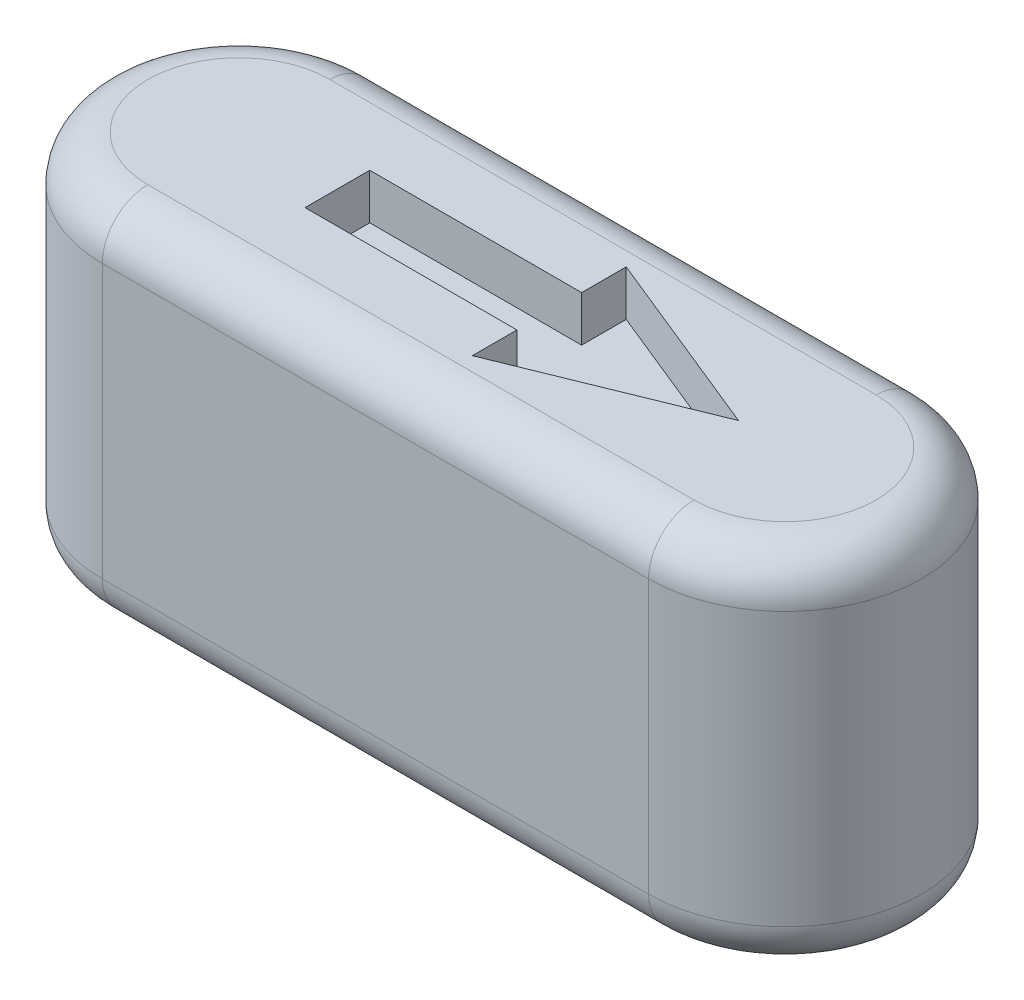
SolidWorks part; units mm, degrees
ref_plane "Front Plane" through (0, 0, 0) normal (0, 0, 1) x (1, 0, 0)
ref_plane "Top Plane" through (0, 0, 0) normal (0, 1, 0) x (1, 0, 0)
ref_plane "Right Plane" through (0, 0, 0) normal (1, 0, 0) x (0, 0, -1)
sketch "Sketch1" plane through (0, 0, 0) normal (0, 1, 0) x (1, 0, 0)
  line L0 (0, 0) -> (15.24, 0) construction
  line L1 (0, 3.81) -> (15.24, 3.81)
  line L2 (0, -3.81) -> (15.24, -3.81)
  arc A0 (0, 3.81) -> (0, -3.81) centre (0, 0) ccw
  arc A1 (15.24, -3.81) -> (15.24, 3.81) centre (15.24, 0) ccw
  point P3 (7.62, 0)
  dimension "D2" = 3.81
  dimension "D1" = 15.24
extrude "Boss-Extrude1" add sketch "Sketch1" along normal blind 10.16
sketch "Sketch2" plane through (0, 10.16, 0) normal (0, 1, 0) x (1, 0, 0)
  line L0 (-3.81, 0) -> (19.05, 0) construction
  line L1 (2.7488, -0.9025) -> (2.7488, 0.9025)
  line L2 (2.7488, 0.9025) -> (8.6602, 0.9025)
  line L3 (8.6602, 0.9025) -> (8.6602, 2.1457)
  line L4 (8.6602, 2.1457) -> (13.9373, 0)
  line L5 (8.6602, -2.1457) -> (13.9373, 0)
  line L6 (8.6602, -0.9025) -> (8.6602, -2.1457)
  line L7 (2.7488, -0.9025) -> (8.6602, -0.9025)
  arc A0 (0, 3.81) -> (0, -3.81) centre (0, 0) ccw construction
  arc A1 (15.24, -3.81) -> (15.24, 3.81) centre (15.24, 0) ccw construction
  point P14 (2.7488, 0)
extrude "Cut-Extrude1" cut sketch "Sketch2" against normal blind 1.27
fillet "Fillet2" radius 1.27 4 edges at (19.05, 10.16, 0) (7.62, 10.16, 3.81) (-3.81, 10.16, 0) (7.62, 10.16, -3.81)
fillet "Fillet3" radius 1.27 4 edges at (19.05, 0, 0) (-3.81, 0, 0) (7.62, 0, 3.81) (7.62, 0, -3.81)
